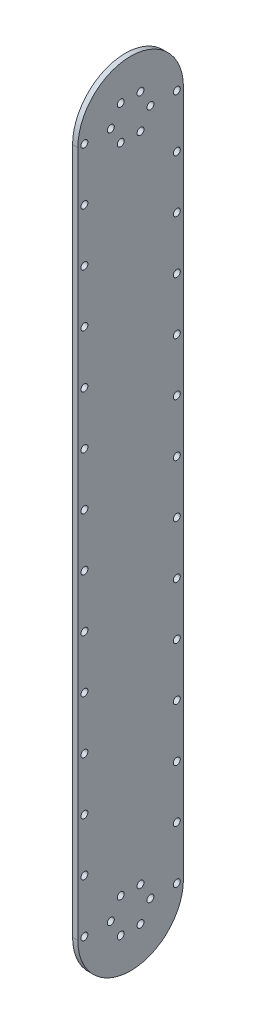
SolidWorks part; units mm, degrees
ref_plane "Front Plane" through (0, 0, 0) normal (1, 0, 0) x (0, 1, 0)
ref_plane "Top Plane" through (0, 0, 0) normal (0, 0, 1) x (0, 1, 0)
ref_plane "Right Plane" through (0, 0, 0) normal (0, 1, 0) x (-1, 0, 0)
sketch "Sketch1" plane through (0, 0, 0) normal (1, 0, 0) x (0, 1, 0)
  line L0 (-208, 0) -> (208, 0) construction
  line L1 (-208, 32) -> (208, 32)
  line L2 (-208, -32) -> (208, -32)
  arc A0 (-208, 32) -> (-208, -32) centre (-208, 0) ccw
  arc A1 (208, -32) -> (208, 32) centre (208, 0) ccw
  point P2 (0, 0)
  dimension "D2" = 32
  dimension "D1" = 416
extrude "Boss-Extrude1" add sketch "Sketch1" along normal blind 3.175
sketch "Sketch2" plane through (3.175, 0, 0) normal (1, 0, 0) x (0, 1, 0)
  arc A0 (208, -32) -> (208, 32) centre (208, 0) ccw construction
  arc A1 (208, -32) -> (209.2294, 31.9764) centre (208, 0) ccw
  circle A2 centre (208, 12) radius 2.1
  circle A3 centre (218.3923, 6) radius 2.1
  circle A4 centre (218.3923, -6) radius 2.1
  circle A5 centre (208, -12) radius 2.1
  circle A6 centre (197.6077, -6) radius 2.1
  circle A7 centre (197.6077, 6) radius 2.1
  dimension "D1" = 4.2
  dimension "D2" = 12
  dimension "D3" = 6
extrude "Cut-Extrude1" cut sketch "Sketch2" against normal through all contours A7 | A2 | A3 | A4 | A5 | A6
sketch "Sketch3" plane through (3.175, 0, 0) normal (1, 0, 0) x (0, 1, 0)
  arc A0 (-208, 32) -> (-208, -32) centre (-208, 0) ccw construction
  arc A1 (-208, 32) -> (-208, -32) centre (-208, 0) ccw
  circle A2 centre (-208, 12) radius 2.1
  circle A3 centre (-197.6077, 6) radius 2.1
  circle A4 centre (-197.6077, -6) radius 2.1
  circle A5 centre (-208, -12) radius 2.1
  circle A6 centre (-218.3923, -6) radius 2.1
  circle A7 centre (-218.3923, 6) radius 2.1
  point P6 (-197.6077, 6)
  dimension "D1" = 4.2
  dimension "D2" = 12
  dimension "D3" = 6
extrude "Cut-Extrude2" cut sketch "Sketch3" against normal blind 10 contours A5 | A4 | A3 | A2 | A7 | A6
sketch "Sketch4" plane through (3.175, 0, 0) normal (1, 0, 0) x (0, 1, 0)
  line L0 (208, 32) -> (-208, 32) construction
  line L1 (0, 0) -> (-240, 0) construction
  circle A0 centre (-208, 12) radius 2.1 construction
  circle A1 centre (-208, 12) radius 2.1
  circle A2 centre (-208, 28) radius 2.1
  arc A3 (-208, 32) -> (-208, -32) centre (-208, 0) ccw construction
  circle A4 centre (-208, -28) radius 2.1
  circle A5 centre (-176, 28) radius 2.1
  circle A6 centre (-176, -28) radius 2.1
  circle A7 centre (-144, 28) radius 2.1
  circle A8 centre (-144, -28) radius 2.1
  circle A9 centre (-112, 28) radius 2.1
  circle A10 centre (-112, -28) radius 2.1
  circle A11 centre (-80, 28) radius 2.1
  circle A12 centre (-80, -28) radius 2.1
  circle A13 centre (-48, 28) radius 2.1
  circle A14 centre (-48, -28) radius 2.1
  circle A15 centre (-16, 28) radius 2.1
  circle A16 centre (-16, -28) radius 2.1
  circle A17 centre (16, 28) radius 2.1
  circle A18 centre (16, -28) radius 2.1
  circle A19 centre (48, 28) radius 2.1
  circle A20 centre (48, -28) radius 2.1
  circle A21 centre (80, 28) radius 2.1
  circle A22 centre (80, -28) radius 2.1
  circle A23 centre (112, 28) radius 2.1
  circle A24 centre (112, -28) radius 2.1
  circle A25 centre (144, 28) radius 2.1
  circle A26 centre (144, -28) radius 2.1
  circle A27 centre (176, 28) radius 2.1
  circle A28 centre (176, -28) radius 2.1
  circle A29 centre (208, 28) radius 2.1
  circle A30 centre (208, -28) radius 2.1
  dimension "D1" = 4.2
  dimension "D2" = 4
  dimension "D4" = 32
  dimension "D3" = 14
extrude "Cut-Extrude3" cut sketch "Sketch4" against normal through all
